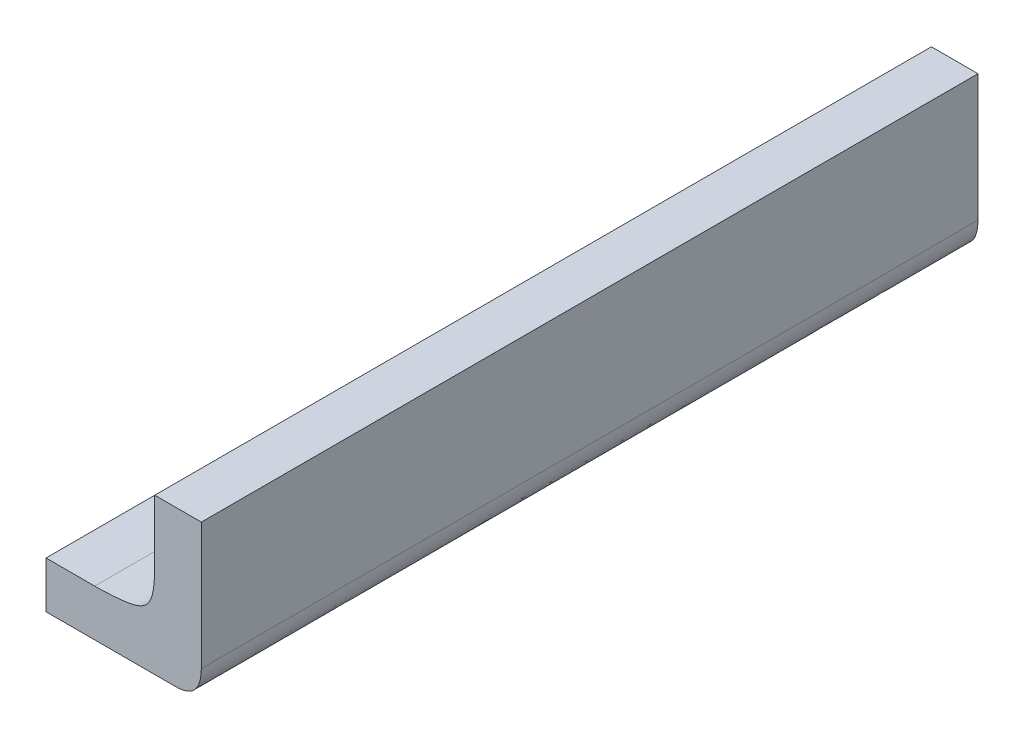
SolidWorks part; units mm, degrees
ref_plane "Front Plane" through (0, 0, 0) normal (0, 0, 1) x (1, 0, 0)
ref_plane "Top Plane" through (0, 0, 0) normal (0, 1, 0) x (1, 0, 0)
ref_plane "Right Plane" through (0, 0, 0) normal (1, 0, 0) x (0, 0, -1)
sketch "Sketch1" plane through (0, 0, 0) normal (0, 0, 1) x (1, 0, 0)
  line L0 (8, -18.4286) -> (5, -18.4286)
  line L3 (-2, -28.4286) -> (6.3752, -28.4286)
  line L4 (8, -18.4286) -> (8, -26.5925)
  line L5 (5, -18.4286) -> (8, -18.4286)
  line L6 (-2, -28.4286) -> (-2, -25.4286)
  line L7 (-2, -25.4286) -> (1.5, -25.4286)
  line L8 (5, -21.9286) -> (5, -18.4286)
  line L9 (5, -18.4286) -> (5, -21.9286)
  spline S0 degree 3 poles (5, -21.9286) (5.0248, -24.832) (4.6482, -25.258) (1.6435, -25.4299) (1.2462, -25.4322) (1.1354, -25.4286) knots 0 0 0 0 0.27448 0.3063 0.318194 0.318194 0.318194 0.318194
  spline S1 degree 2 poles (8, -26.5517) (8.009, -28.4145) (6.3752, -28.4286) knots 0 0 0 1 1 1
  dimension "D2" = 3
  dimension "D3" = 3
extrude "Boss-Extrude1" add sketch "Sketch1" along normal blind 50 contours L8 S0 L7 L6 L3 L4 L0
